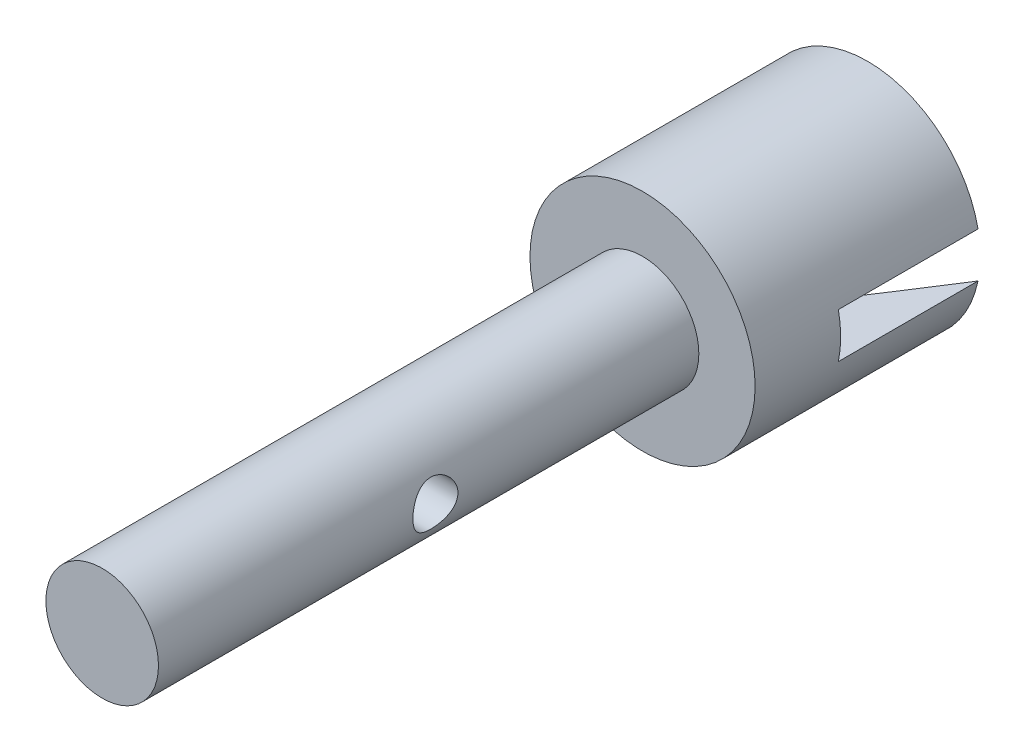
SolidWorks part; units mm, degrees
material "PBT General Purpose"
ref_plane "Front" through (0, 0, 0) normal (0, 0, 1) x (1, 0, 0)
ref_plane "Top" through (0, 0, 0) normal (0, 1, 0) x (1, 0, 0)
ref_plane "Right" through (0, 0, 0) normal (1, 0, 0) x (0, 0, -1)
sketch "Sketch1" plane through (0, 0, 0) normal (0, 0, 1) x (1, 0, 0)
  circle A0 centre (0, 0) radius 5
extrude "Boss-Extrude1" add sketch "Sketch1" along normal blind 10
sketch "Sketch2" plane through (0, 0, 10) normal (0, 0, 1) x (1, 0, 0)
  circle A0 centre (0, 0) radius 2.5
extrude "Boss-Extrude2" add sketch "Sketch2" along normal blind 24
cosmetic thread "Cosmetic Thread1" parameters "D1"=6, "D2"=4.11
sketch "Sketch3" plane through (0, 0, 0) normal (0, 0, -1) x (-1, 0, 0)
  circle A0 centre (0, 0) radius 3
extrude "Cut-Extrude1" cut sketch "Sketch3" against normal blind 5.2
chamfer "Chamfer1" distance 3.2 angle 32 1 edges at (-3, 0, 0)
sketch "Sketch6" plane through (0, 0, 5.2) normal (0, 0, -1) x (-1, 0, 0)
  line L0 (-3, 0) -> (3, 0) construction
  line L1 (3, 0) -> (-3, 0)
  circle A0 centre (0, 0) radius 3 construction
  arc A1 (3, 0) -> (-3, 0) centre (0, 0) cw
revolve "Cut-Revolve2" cut sketch "Sketch6" angle 360 about L1
sketch "Sketch7" plane through (0, 0, 0) normal (0, 0, 1) x (1, 0, 0)
  line L1 (6.0763, -1) -> (-6.0763, -1)
  line L2 (6.0763, -1) -> (6.0763, 1)
  line L3 (6.0763, 1) -> (-6.0763, 1)
  line L4 (-6.0763, -1) -> (-6.0763, 1)
  line L5 (6.0763, -1) -> (-6.0763, 1) construction
  line L6 (6.0763, 1) -> (-6.0763, -1) construction
  point P0 (0, 0)
  dimension "D1" = 2
extrude "Cut-Extrude2" cut sketch "Sketch7" along normal blind 6.2
ref_plane "Plane2" through (2.5, 0, 0) normal (1, 0, 0) x (0, 0, -1)
sketch "Sketch8" plane through (2.5, 0, 0) normal (1, 0, 0) x (0, 0, -1)
  line L0 (-34, 2.5) -> (-34, -2.5) construction
  circle A0 centre (-21.7, 0) radius 1
  dimension "D1" = 2
  dimension "D2" = 12.3
extrude "Cut-Extrude3" cut sketch "Sketch8" against normal up to next
